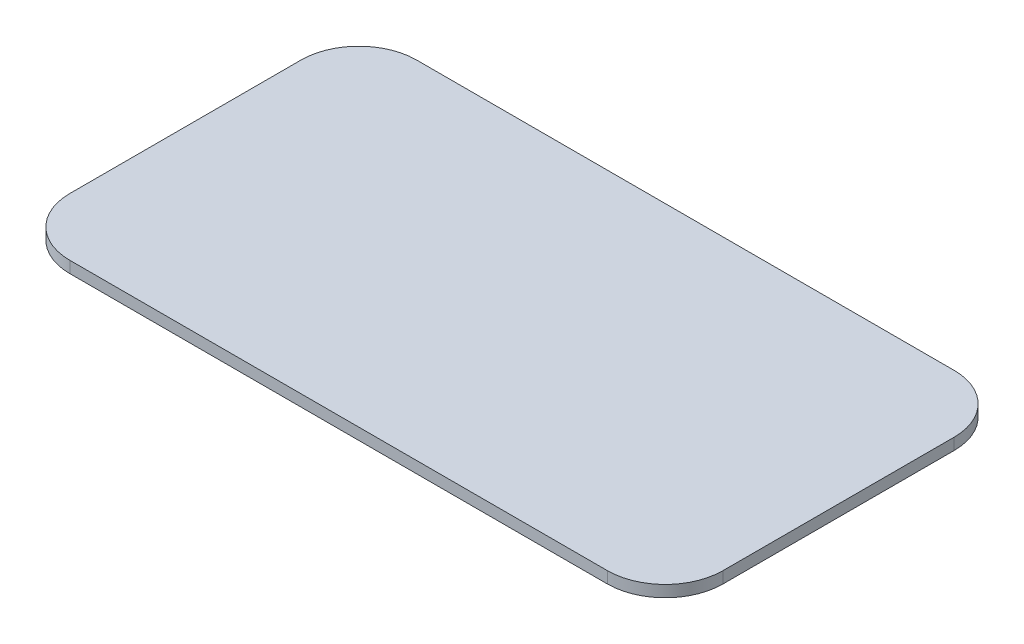
SolidWorks part; units mm, degrees
material "ABS"
ref_plane "Plano frontal" through (0, 0, 0) normal (0, 0, 1) x (1, 0, 0)
ref_plane "Plano superior" through (0, 0, 0) normal (0, 1, 0) x (1, 0, 0)
ref_plane "Plano direito" through (0, 0, 0) normal (1, 0, 0) x (0, 0, -1)
sketch "Esboço1" plane through (0, 0, 0) normal (0, 1, 0) x (1, 0, 0)
  line L1 (-13.2145, 15.5332) -> (79.7855, 15.5332)
  line L2 (-23.2145, 5.5332) -> (-23.2145, -34.4668)
  line L3 (-13.2145, -44.4668) -> (79.7855, -44.4668)
  line L4 (89.7855, 5.5332) -> (89.7855, -34.4668)
  arc A0 (89.7855, 5.5332) -> (79.7855, 15.5332) centre (79.7855, 5.5332) ccw
  arc A1 (89.7855, -34.4668) -> (79.7855, -44.4668) centre (79.7855, -34.4668) cw
  arc A2 (-13.2145, -44.4668) -> (-23.2145, -34.4668) centre (-13.2145, -34.4668) cw
  arc A3 (-23.2145, 5.5332) -> (-13.2145, 15.5332) centre (-13.2145, 5.5332) cw
  point P4 (33.2855, 15.5332)
  point P7 (89.7855, 15.5332)
  point P12 (-23.2145, -44.4668)
  point P15 (-23.2145, 15.5332)
  dimension "D4" = 10
  dimension "D1" = 113
  dimension "D2" = 56.5
  dimension "D3" = 60
extrude "Ressalto-extrusão1" add sketch "Esboço1" along normal blind 2
